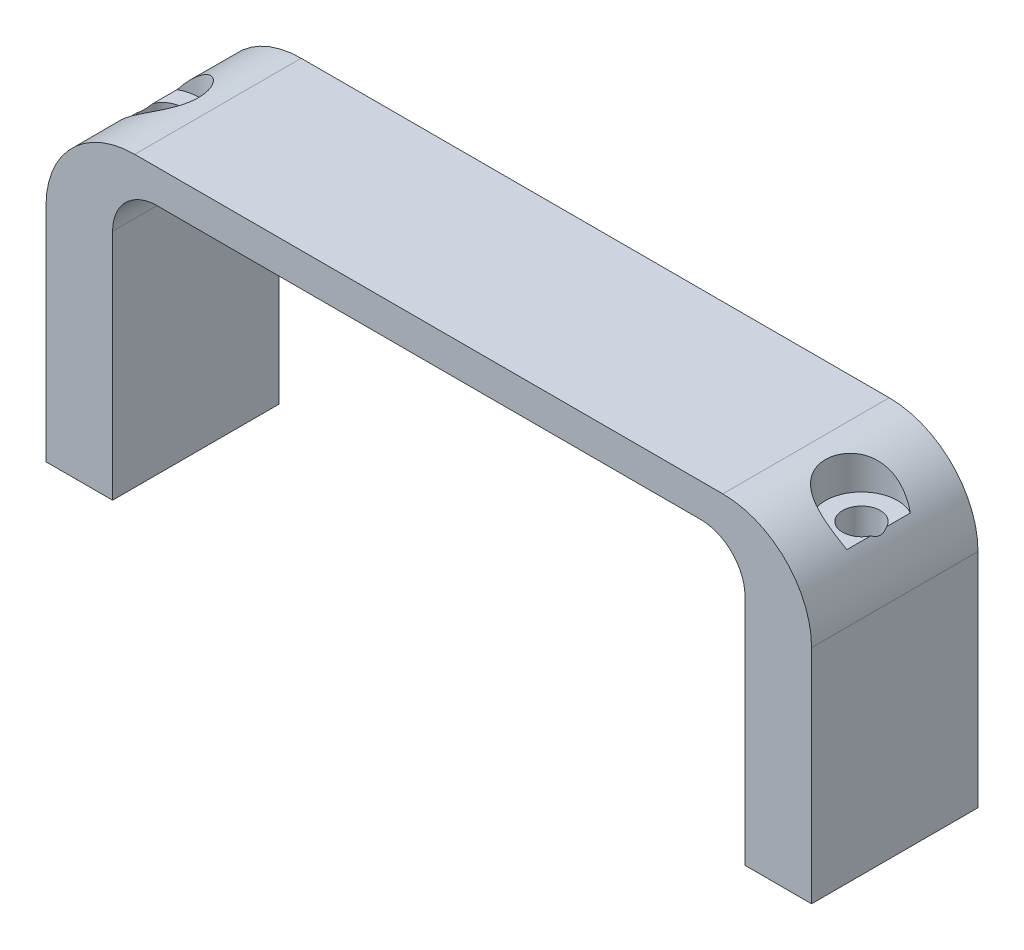
SolidWorks part; units mm, degrees
ref_plane "Přední rovina" through (0, 0, 0) normal (0, 0, 1) x (1, 0, 0)
ref_plane "Horní rovina" through (0, 0, 0) normal (0, 1, 0) x (1, 0, 0)
ref_plane "Pravá rovina" through (0, 0, 0) normal (1, 0, 0) x (0, 0, -1)
sketch "Skica1" plane through (0, 0, 0) normal (0, 0, 1) x (1, 0, 0)
  line L0 (-23.7718, 0) -> (29.2282, 0)
  line L1 (37.2282, -8) -> (37.2282, -28)
  line L2 (37.2282, -28) -> (31.2282, -28)
  line L3 (31.2282, -28) -> (31.2282, -7)
  line L4 (27.2282, -3) -> (-21.7718, -3)
  line L5 (-25.7718, -7) -> (-25.7718, -28)
  line L6 (-25.7718, -28) -> (-31.7718, -28)
  line L7 (-31.7718, -8) -> (-31.7718, -28)
  arc A0 (31.2282, -7) -> (27.2282, -3) centre (27.2282, -7) ccw
  arc A1 (-21.7718, -3) -> (-25.7718, -7) centre (-21.7718, -7) ccw
  arc A2 (29.2282, 0) -> (37.2282, -8) centre (29.2282, -8) cw
  arc A3 (-23.7718, 0) -> (-31.7718, -8) centre (-23.7718, -8) ccw
  point P13 (-25.7718, -3)
  point P16 (37.2282, 0)
  point P19 (-31.7718, 0)
  dimension "D5" = 4
  dimension "D6" = 8
  dimension "D1" = 69
  dimension "D2" = 6
  dimension "D3" = 28
  dimension "D4" = 25
extrude "Přidat vysunutím1" add sketch "Skica1" along normal blind 15
sketch "Skica2" plane through (0, 0, 0) normal (0, 1, 0) x (1, 0, 0)
  line L0 (2.7282, -15) -> (2.7282, 0)
  line L1 (29.2282, -15) -> (-23.7718, -15) construction
  line L2 (29.2282, 0) -> (-23.7718, 0) construction
  line L3 (-28.7718, -7.5) -> (34.2282, -7.5)
  point P9 (2.7282, -7.5)
  dimension "D1" = 31.5
hole_wizard "Válcové zahloubení pro M3 šrouby s vnitřním šestihranem1" positions "Skica3" profile "Skica4" counterbore size "M3" standard "DIN" end condition through all
sketch "Skica3" plane through (0, 0, 0) normal (0, 1, 0) x (1, 0, 0)
  point P0 (-28.7718, -7.5)
  point P3 (34.2282, -7.5)
sketch "Skica4" plane through (-28.7718, 0, 7.5) normal (1, 0, 0) x (0, 0, 1)
  line L0 (0, 0) -> (0, 28)
  line L1 (0, 28) -> (1.7, 28)
  line L3 (1.7, 28) -> (1.7, 3.4)
  line L4 (1.7, 3.4) -> (3.25, 3.4)
  line L5 (3.25, 3.4) -> (3.25, 0)
  line L7 (3.25, 0) -> (0, 0)
  line L11 (0, -6.35) -> (0, 107.95) construction
  dimension "Průměr díry skrz" = 3.4
  dimension "Hloubka díry skrz" = 28
  dimension "Průměr válcového zahloubení" = 6.5
  dimension "Hloubka válcového zahloubení" = 3.4
